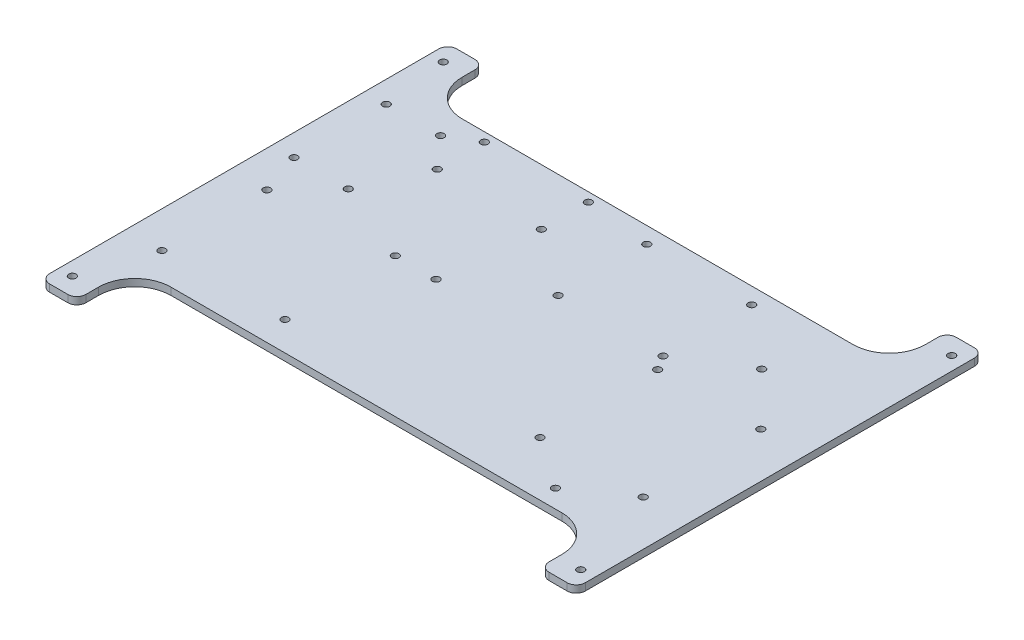
SolidWorks part; units mm, degrees
ref_plane "Front Plane" through (0, 0, 0) normal (0, 0, 1) x (1, 0, 0)
ref_plane "Top Plane" through (0, 0, 0) normal (0, 1, 0) x (1, 0, 0)
ref_plane "Right Plane" through (0, 0, 0) normal (1, 0, 0) x (0, 0, -1)
sketch "Sketch1" plane through (0, 0, 0) normal (0, 1, 0) x (1, 0, 0)
  line L0 (128, 112.5) -> (148, 112.5)
  line L1 (-148, -112.5) -> (-128, -112.5)
  line L2 (-148, -112.5) -> (-148, 112.5)
  line L3 (-148, 112.5) -> (-128, 112.5)
  line L4 (148, -112.5) -> (148, 112.5)
  line L5 (-148, -112.5) -> (148, 112.5) construction
  line L6 (-148, 112.5) -> (148, -112.5) construction
  line L8 (-128, 112.5) -> (-128, 80.5)
  line L9 (-128, 80.5) -> (128, 80.5)
  line L10 (128, 112.5) -> (128, 80.5)
  line L12 (-128, -112.5) -> (-128, -80.5)
  line L13 (-128, -80.5) -> (128, -80.5)
  line L14 (128, -112.5) -> (128, -80.5)
  line L15 (128, -112.5) -> (148, -112.5)
  point P0 (0, 0)
  dimension "D1" = 225
  dimension "D2" = 296
  dimension "D3" = 20
  dimension "D4" = 20
  dimension "D5" = 32
extrude "Boss-Extrude1" add sketch "Sketch1" along normal blind 4
fillet "Fillet1" radius 5 8 edges at (-148, 2, 112.5) (-148, 2, -112.5) (148, 2, -112.5) (148, 2, 112.5) (128, 2, -112.5) (128, 2, 112.5) (-128, 2, -112.5) (-128, 2, 112.5)
fillet "Fillet2" radius 20 4 edges at (-128, 2, 80.5) (128, 2, 80.5) (-128, 2, -80.5) (128, 2, -80.5)
sketch "Sketch3" plane through (0, 4, 0) normal (0, 1, 0) x (1, 0, 0)
  circle A1 centre (-140.5, 102.5) radius 2
  circle A3 centre (140.5, 102.5) radius 2
  circle A5 centre (140.5, -102.5) radius 2
  circle A7 centre (-140.5, -102.5) radius 2
  dimension "D1" = 4
extrude "Cut-Extrude1" cut sketch "Sketch3" against normal blind 5
sketch "Sketch4" plane through (0, 4, 0) normal (0, 1, 0) x (1, 0, 0)
  line L0 (-148, 107.5) -> (-148, -107.5) construction
  line L1 (108, 80.5) -> (-108, 80.5) construction
  line L2 (148, -107.5) -> (148, 107.5) construction
  line L3 (-108, -80.5) -> (108, -80.5) construction
  circle A0 centre (-136, 66.5) radius 2
  circle A1 centre (-136, 15.5) radius 2
  circle A2 centre (-106, 15.5) radius 2
  circle A3 centre (-106, 66.5) radius 2
  circle A4 centre (-90.8, 75.5) radius 2
  circle A5 centre (-90.8, 49.5) radius 2
  circle A6 centre (-33.3, 75.5) radius 2
  circle A7 centre (-33.3, 49.5) radius 2
  circle A8 centre (3, 71.5) radius 2
  circle A9 centre (61, 71.5) radius 2
  circle A10 centre (61, 22.5) radius 2
  circle A11 centre (3, 22.5) radius 2
  circle A12 centre (66, 14.5) radius 2
  circle A13 centre (123, 14.5) radius 2
  circle A14 centre (123, -50.5) radius 2
  circle A15 centre (66, -50.5) radius 2
  circle A16 centre (94.5, 43.5) radius 2
  circle A17 centre (94.5, -70.5) radius 2
  circle A18 centre (-128, -7.5) radius 2
  circle A19 centre (-128, -65.5) radius 2
  circle A20 centre (-61, -64.5) radius 2
  circle A22 centre (-61, -3.5) radius 2
  circle A23 centre (-38.5, -3.5) radius 2
  point P56 (0, 0)
  point P57 (0, 0)
  dimension "D1" = 4
  dimension "D6" = 4
  dimension "D12" = 4
  dimension "D16" = 4
  dimension "D24" = 4
  dimension "D28" = 4
  dimension "D2" = 30
  dimension "D3" = 51
  dimension "D4" = 12
  dimension "D5" = 14
  dimension "D7" = 57.5
  dimension "D8" = 26
  dimension "D9" = 57.2
  dimension "D10" = 5
  dimension "D11" = 9
  dimension "D13" = 58
  dimension "D14" = 49
  dimension "D15" = 87
  dimension "D17" = 65
  dimension "D18" = 57
  dimension "D19" = 114
  dimension "D20" = 25
  dimension "D21" = 28.5
  dimension "D22" = 10
  dimension "D23" = 20
  dimension "D25" = 58
  dimension "D26" = 20
  dimension "D27" = 15
  dimension "D29" = 22.5
  dimension "D30" = 16
  dimension "D31" = 87
  dimension "D32" = 61
extrude "Cut-Extrude2" cut sketch "Sketch4" against normal blind 10
sketch "Sketch5" plane through (0, 0, 0) normal (0, -1, 0) x (1, 0, 0)
  line L0 (-108, 80.5) -> (108, 80.5) construction
  line L1 (131, 44.5) -> (-131, 44.5)
  line L2 (131, 44.5) -> (131, 36.5)
  line L3 (131, 36.5) -> (-131, 36.5)
  line L4 (-131, 44.5) -> (-131, 36.5)
  line L5 (-131, -1.5) -> (131, -1.5)
  line L6 (-131, -1.5) -> (-131, -9.5)
  line L7 (-131, -9.5) -> (131, -9.5)
  line L8 (131, -1.5) -> (131, -9.5)
  line L9 (-131, -61.5) -> (131, -61.5)
  line L10 (-131, -61.5) -> (-131, -53.5)
  line L11 (-131, -53.5) -> (131, -53.5)
  line L12 (131, -61.5) -> (131, -53.5)
  line L13 (108, -80.5) -> (-108, -80.5) construction
  line L14 (148, 107.5) -> (148, -107.5) construction
  line L15 (-148, -107.5) -> (-148, 107.5) construction
  dimension "D1" = 36
  dimension "D2" = 19
  dimension "D3" = 44
  dimension "D4" = 8
  dimension "D5" = 8
  dimension "D6" = 8
  dimension "D7" = 17
  dimension "D8" = 17
extrude "Boss-Extrude2" add sketch "Sketch5" along normal blind 4
